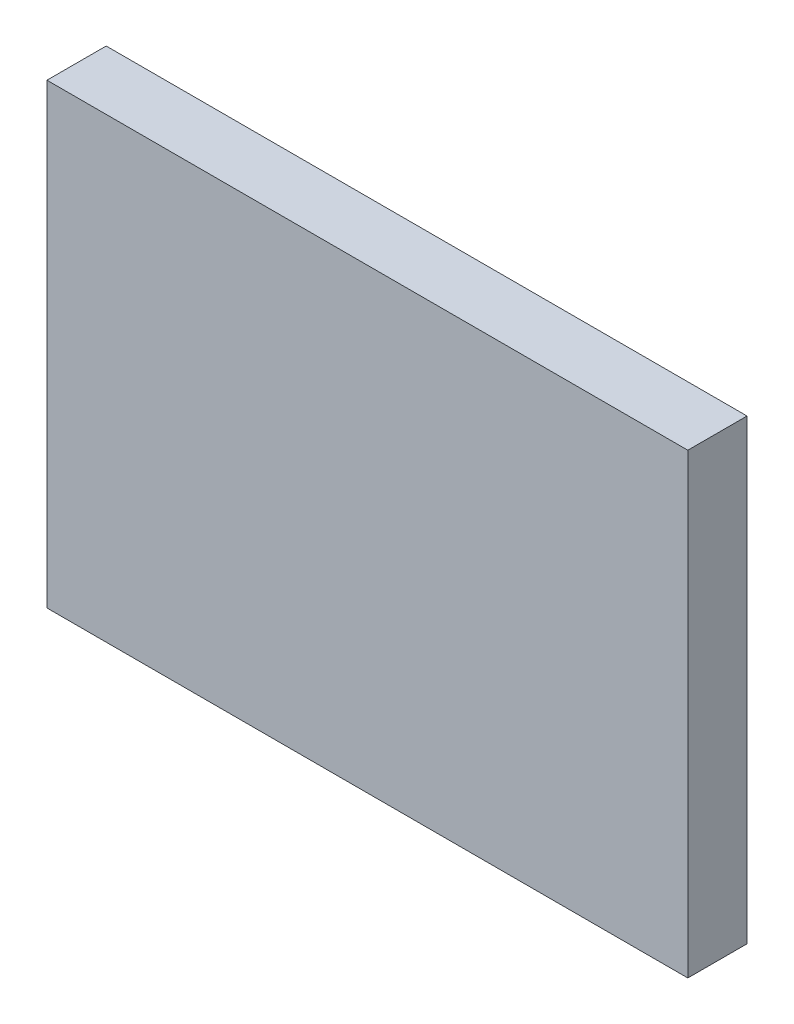
SolidWorks part; units mm, degrees
ref_plane "Front Plane" through (0, 0, 0) normal (0, 0, 1) x (1, 0, 0)
ref_plane "Top Plane" through (0, 0, 0) normal (0, 1, 0) x (1, 0, 0)
ref_plane "Right Plane" through (0, 0, 0) normal (1, 0, 0) x (0, 0, -1)
sketch "Sketch1" plane through (0, 0, 0) normal (0, 0, 1) x (1, 0, 0)
  line B0 (-68.7, 49) -> (-68.7, 0)
  line B1 (-68.7, 0) -> (0, 0)
  line B2 (0, 0) -> (0, 49)
  line B3 (0, 49) -> (-68.7, 49)
sketch_block_instance "Divider_OC-1"
sketch_block "Divider_OC"
extrude "Boss-Extrude1" add sketch "Sketch1" along normal blind 6.35
sketch "Sketch2" plane through (0, 0, 0) normal (0, -1, 0) x (1, 0, 0)
  line L4 (-68.7, 0) -> (0, 0)
  line L5 (0, 0) -> (0, 6.35)
  line L6 (0, 6.35) -> (-68.7, 6.35)
  line L7 (-68.7, 6.35) -> (-68.7, 0)
  line L8 (-68.7, 0) -> (0, 0)
  line L9 (0, 0) -> (0, 6.35)
  line L10 (0, 6.35) -> (-68.7, 6.35)
  line L11 (-68.7, 6.35) -> (-68.7, 0)
  dimension "D1" = 0
